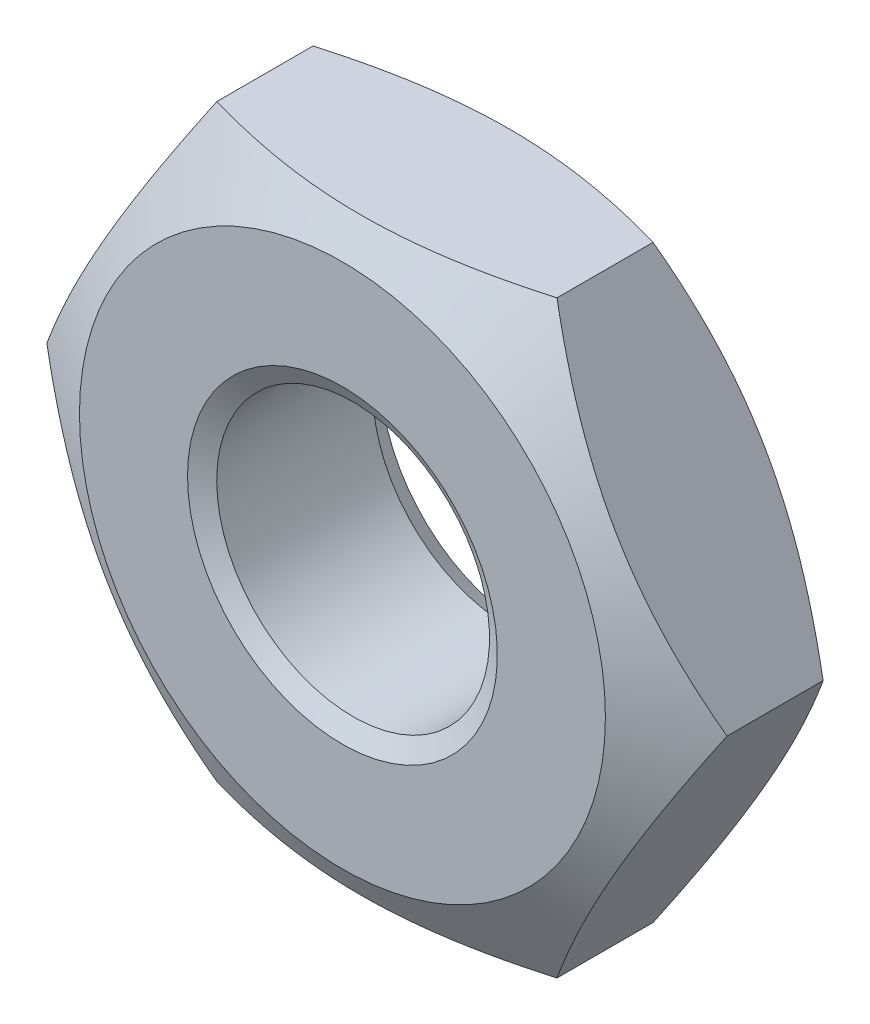
SolidWorks part; units mm, degrees
ref_plane "Front" through (0, 0, 0) normal (0, 0, 1) x (1, 0, 0)
ref_plane "Top" through (0, 0, 0) normal (0, 1, 0) x (1, 0, 0)
ref_plane "Right" through (0, 0, 0) normal (1, 0, 0) x (0, 0, -1)
sketch "Sketch1" plane through (0, 0, 0) normal (0, 0, 1) x (1, 0, 0)
  line L1 (2.0207, -3.5) -> (4.0415, 0)
  line L2 (4.0415, 0) -> (2.0207, 3.5)
  line L3 (2.0207, 3.5) -> (-2.0207, 3.5)
  line L4 (-2.0207, 3.5) -> (-4.0415, 0)
  line L5 (-4.0415, 0) -> (-2.0207, -3.5)
  line L6 (-2.0207, -3.5) -> (2.0207, -3.5)
  circle A0 centre (0, 0) radius 3.5 construction
  circle A1 centre (0, 0) radius 1.621
  dimension "D" = 3.242
  dimension "s" = 7
extrude "BaseNut" add sketch "Sketch1" against normal blind 2.2
cosmetic thread "ThreadCosmetic1" [suppressed] parameters "D"=4
sketch "Sketch2" plane through (0, 0, 0) normal (0, 1, 0) x (1, 0, 0)
  line L0 (-4.0415, 2.2) -> (-3.125, 2.2)
  line L2 (-3.125, 2.2) -> (-4.0415, 1.6709)
  line L3 (-4.0415, 1.6709) -> (-4.0415, 2.2)
  line L4 (0, 3.3759) -> (0, -9.8171) construction
  line L6 (-9.7712, 1.1) -> (9.8853, 1.1) construction
  line L7 (-4.0415, 0.5291) -> (-4.0415, 0)
  line L8 (-3.125, 0) -> (-4.0415, 0.5291)
  line L9 (-4.0415, 0) -> (-3.125, 0)
  dimension "dw" = 6.25
  dimension "D1" = 30
  dimension "D2" = 1.1
revolve "Double-Chamfer" cut sketch "Sketch2" angle 360 about L4
chamfer "EndChamfer" distance 0.22 angle 30 2 edges at (1.621, 0, -2.2) (1.621, 0, 0)
sketch "Sketch3" plane through (0, 0, 0) normal (0, 1, 0) x (1, 0, 0)
  line L0 (0, 6.7075) -> (0, -2.1252) construction
  line L1 (1.242, 2.1695) -> (1.621, 2.1695)
  line L2 (1.621, 2.1695) -> (1.9492, 1.98)
  line L3 (1.9492, 1.98) -> (1.621, 1.7905)
  line L4 (1.621, 1.7905) -> (1.242, 1.7905)
  line L5 (1.242, 1.7905) -> (1.242, 2.1695)
  line L6 (1.621, 1.98) -> (-1.621, 1.98) construction
  dimension "D1" = 0.379
  dimension "D2" = 3.242
revolve "Cut-Revolve10" [suppressed] cut sketch "Sketch3" angle 360 about L0
pattern_linear "LPattern10" [suppressed] count 4 spacing 0.4548 along (0, 0, 1)
equation "\"dw@Sketch2\" = \"s@Sketch1\"-0.75"
equation "\"D2@Sketch2\" = \"m@BaseNut\" / 2"
equation "\"D1@EndChamfer\" = \"m@BaseNut\" / 10"
equation "\"D2@Sketch3\" = \"D@Sketch1\""
equation "\"D1@Sketch3\" = (  \"D@ThreadCosmetic1\" - \"D@Sketch1\" )  / 2"
equation "\"D3@LPattern10\" = \"D1@Sketch3\" * 1.2"
equation "\"D1@LPattern10\" = (  \"m@BaseNut\" - \"D1@EndChamfer\" )  / \"D3@LPattern10\" "
